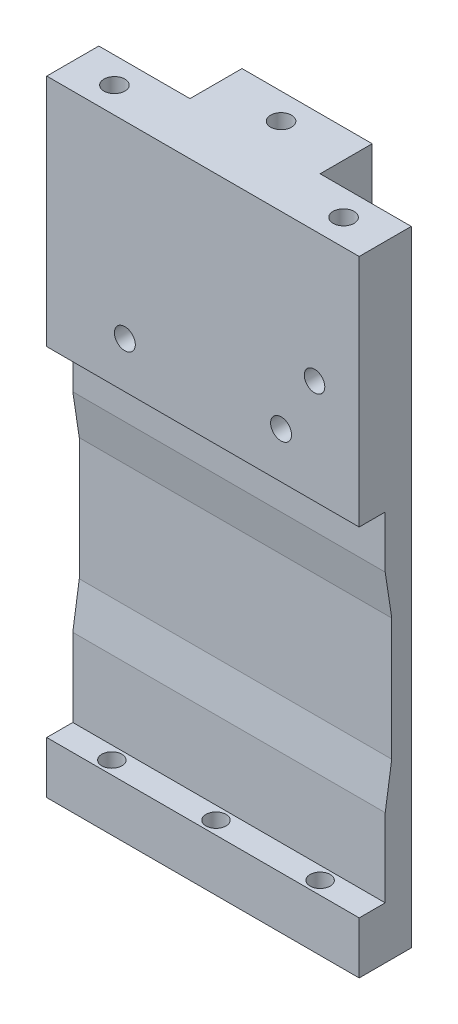
SolidWorks part; units mm, degrees
material "6061 Alloy"
ref_plane "Front Plane" through (0, 0, 0) normal (0, 0, 1) x (1, 0, 0)
ref_plane "Top Plane" through (0, 0, 0) normal (0, 1, 0) x (1, 0, 0)
ref_plane "Right Plane" through (0, 0, 0) normal (1, 0, 0) x (0, 0, -1)
sketch "Sketch1" plane through (0, 0, 0) normal (0, 1, 0) x (1, 0, 0)
  line L0 (-15.875, 6.35) -> (-15.875, 19.05)
  line L1 (38.1, -6.35) -> (-38.1, -6.35)
  line L2 (38.1, -6.35) -> (38.1, 6.35)
  line L3 (38.1, 6.35) -> (15.875, 6.35)
  line L4 (-38.1, -6.35) -> (-38.1, 6.35)
  line L5 (38.1, -6.35) -> (-38.1, 6.35) construction
  line L6 (38.1, 6.35) -> (-38.1, -6.35) construction
  line L7 (-15.875, 19.05) -> (15.875, 19.05)
  line L8 (15.875, 19.05) -> (15.875, 6.35)
  line L9 (-15.875, 6.35) -> (-38.1, 6.35)
  line L10 (0, 19.05) -> (0, 0) construction
  point P0 (0, 0)
  dimension "D1" = 76.2
  dimension "D2" = 12.7
  dimension "D3" = 31.75
  dimension "D4" = 12.7
extrude "Boss-Extrude1" add sketch "Sketch1" along normal mid plane 152.4
ref_plane "Plane1" through (0, 0, 0) normal (0, 1, 0) x (1, 0, 0)
sketch "Sketch5" plane through (0, 0, 0) normal (0, 1, 0) x (1, 0, 0)
  line L0 (-4.7625, 19.05) -> (-4.7625, 12.7)
  line L1 (15.875, 19.05) -> (-15.875, 19.05) construction
  line L2 (4.7625, 12.7) -> (4.7625, 19.05)
  line L3 (0, 0) -> (0, 12.7) construction
  line L4 (-4.7625, 19.05) -> (4.7625, 19.05)
  arc A0 (-4.7625, 12.7) -> (4.7625, 12.7) centre (0, 12.7) ccw
  point P10 (0, 7.9375)
  dimension "D1" = 11.1125
  dimension "D2" = 9.525
extrude "Cut-Extrude3" cut sketch "Sketch5" against normal mid plane 95.25
sketch "Sketch9" plane through (0, 0, 0) normal (1, 0, 0) x (0, 0, -1)
  line L0 (19.05, -52.3875) -> (12.7, -52.3875)
  line L1 (19.05, -52.3875) -> (19.05, -47.625)
  line L2 (19.05, -47.625) -> (7.9375, -47.625) construction
  line L3 (12.7, -52.3875) -> (12.7, -47.625) construction
  line L4 (7.9375, -47.625) -> (19.05, -47.625)
  arc A0 (12.7, -52.3875) -> (7.9375, -47.625) centre (12.7, -47.625) cw
  dimension "D2" = 90
  dimension "D1" = 4.7625
  dimension "D3" = 11.1125
revolve "Cut-Revolve1" cut sketch "Sketch9" angle 360 about L4
mirror "Mirror1" about plane through (0, 0, 0) normal (0, 1, 0) of "Cut-Revolve1"
ref_plane "Parting Plane" through (0, 0, 0) normal (0, 0, 1) x (1, 0, 0)
sketch "Sketch12" plane through (38.1, 0, 0) normal (1, 0, 0) x (0, 0, -1)
  line L0 (-6.35, -63.5) -> (0, -63.5)
  line L1 (-6.35, 76.2) -> (-6.35, -76.2) construction
  line L2 (0, 45.4834) -> (0, -45.4834) construction
  line L3 (0, -63.5) -> (0, -44.45)
  line L4 (0, -44.45) -> (1.5875, -33.9561)
  line L5 (1.5875, -33.9561) -> (1.5875, -4.1439)
  line L6 (1.5875, -4.1439) -> (0, 6.35)
  line L7 (0, 6.35) -> (0, 19.05)
  line L8 (0, 19.05) -> (-6.35, 19.05)
  line L9 (-6.35, 19.05) -> (-6.35, -63.5)
  line L10 (-6.35, -76.2) -> (6.35, -76.2) construction
  dimension "D1" = 19.05
  dimension "D2" = 12.7
  dimension "D3" = 82.55
  dimension "D4" = 1.5875
  dimension "D5" = 12.7
extrude "Cut-Extrude4" cut sketch "Sketch12" against normal through all
hole_wizard "#10 (0.1935) Diameter Hole1" positions "Sketch15" profile "Sketch16" hole size "#10" standard "ANSI Inch"
sketch "Sketch15" plane through (0, -76.2, 0) normal (0, -1, 0) x (-1, 0, 0)
  line L0 (38.1, 6.35) -> (38.1, -6.35) construction
  line L1 (-38.1, -6.35) -> (-38.1, 6.35) construction
  line L3 (25.4, -3.175) -> (-25.4, -3.175) construction
  line L4 (38.1, -6.35) -> (-38.1, -6.35) construction
  point P0 (25.4, -3.175)
  point P2 (-25.4, -3.175)
  point P16 (0, -3.175)
  dimension "D1" = 12.7
  dimension "D2" = 12.7
  dimension "D3" = 3.175
sketch "Sketch16" plane through (-25.4, -76.2, 3.175) normal (1, 0, 0) x (0, 0, -1)
  line L0 (0, 0) -> (0, 20.5266)
  line L1 (0, 20.5266) -> (2.4574, 19.05)
  line L2 (2.4574, 19.05) -> (2.4574, 0)
  line L5 (2.4574, 0) -> (0, 0)
  line L10 (0, 20.5266) -> (-2.4575, 19.05) construction
  line L11 (0, -6.35) -> (0, 107.95) construction
  dimension "Hole Dia." = 4.9149
  dimension "Hole Depth" = 19.05
  dimension "Drill Angle" = 118
hole_wizard "1/4-20 Tapped Hole1" positions "Sketch17" profile "Sketch18" tap size "1/4-20" standard "ANSI Inch" end condition through all
sketch "Sketch17" plane through (0, 76.2, 0) normal (0, 1, 0) x (1, 0, 0)
  line L0 (15.875, 19.05) -> (-15.875, 19.05) construction
  line L1 (15.875, 6.35) -> (15.875, 19.05) construction
  point P0 (0, 12.7)
  dimension "D1" = 6.35
  dimension "D2" = 15.875
sketch "Sketch18" plane through (0, 76.2, -12.7) normal (1, 0, 0) x (0, 0, 1)
  line L0 (0, 0) -> (0, 152.4)
  line L1 (0, 152.4) -> (2.5527, 152.4)
  line L2 (2.5527, 152.4) -> (2.5527, 0)
  line L5 (2.5527, 0) -> (0, 0)
  line L11 (0, -6.35) -> (0, 107.95) construction
  dimension "Thru Tap Drill Dia." = 5.1054
  dimension "Thru Tap Drill Depth" = 152.4
cosmetic thread "Hole Thread1" parameters "D2"=6.35
ref_plane "Plane2" through (0, -19.05, 0) normal (0, -1, 0) x (-1, 0, 0)
sketch "Sketch19" plane through (0, 0, -6.35) normal (0, 0, -1) x (-1, 0, 0)
  line L1 (-18.7294, -19.05) -> (18.7294, -19.05) construction
  circle A0 centre (-27.209, 44.45) radius 2.5
  dimension "D1" = 5
  dimension "D2" = 63.5
extrude "Cut-Extrude5" cut sketch "Sketch19" against normal through all
hole_wizard "1/4-20 Tapped Hole2" positions "Sketch20" profile "Sketch21" tap size "1/4-20" standard "ANSI Inch"
sketch "Sketch20" plane through (0, 76.2, 0) normal (0, 1, 0) x (1, 0, 0)
  point P0 (27.94, 0)
  point P3 (-27.94, 0)
sketch "Sketch21" plane through (27.94, 76.2, 0) normal (1, 0, 0) x (0, 0, 1)
  line L0 (0, 0) -> (0, 22.225)
  line L1 (0, 22.225) -> (2.5527, 20.6912)
  line L2 (2.5527, 20.6912) -> (2.5527, 0)
  line L5 (2.5527, 0) -> (0, 0)
  line L10 (0, 22.225) -> (-2.5527, 20.6912) construction
  line L11 (0, -6.35) -> (0, 107.95) construction
  dimension "Tap Drill Dia." = 5.1054
  dimension "Tap Drill Depth" = 22.225
  dimension "Drill Angle" = 118
cosmetic thread "Hole Thread2" parameters "D1"=38.26, "D2"=6.35
cosmetic thread "Hole Thread3" parameters "D1"=38.26, "D2"=6.35
hole_wizard "1/4-20 Tapped Hole3" positions "Sketch22" profile "Sketch23" tap size "1/4-20" standard "ANSI Inch"
sketch "Sketch22" plane through (0, 0, -19.05) normal (0, 0, -1) x (-1, 0, 0)
  line L0 (9.525, 57.15) -> (-9.525, 57.15) construction
  line L2 (0, 57.15) -> (0, 0) construction
  line L4 (-15.875, -76.2) -> (15.875, -76.2) construction
  line L5 (-9.525, 57.15) -> (-9.525, -66.675) construction
  line L7 (-9.525, -66.675) -> (9.525, -66.675) construction
  point P0 (-9.525, -66.675)
  point P2 (9.525, 57.15)
  point P4 (-9.525, 57.15)
  point P26 (9.525, -66.675)
  dimension "D1" = 19.05
  dimension "D2" = 123.825
  dimension "D3" = 9.525
  dimension "D4" = 19.05
sketch "Sketch23" plane through (9.525, -66.675, -19.05) normal (1, 0, 0) x (0, 1, 0)
  line L0 (0, 0) -> (0, 10.5838)
  line L1 (0, 10.5838) -> (2.5527, 9.05)
  line L2 (2.5527, 9.05) -> (2.5527, 0)
  line L5 (2.5527, 0) -> (0, 0)
  line L10 (0, 10.5838) -> (-2.5527, 9.05) construction
  line L11 (0, -6.35) -> (0, 107.95) construction
  dimension "Tap Drill Dia." = 5.1054
  dimension "Tap Drill Depth" = 9.05
  dimension "Drill Angle" = 118
cosmetic thread "Hole Thread4" parameters "D1"=38.26, "D2"=6.35
cosmetic thread "Hole Thread5" parameters "D1"=38.26, "D2"=6.35
cosmetic thread "Hole Thread6" parameters "D1"=38.26, "D2"=6.35
cosmetic thread "Hole Thread9" parameters "D1"=38.26, "D2"=6.35
hole_wizard "1/4-20 Tapped Hole4" positions "Sketch24" profile "Sketch25" tap size "1/4-20" standard "ANSI Inch"
sketch "Sketch24" plane through (0, 0, 6.35) normal (0, 0, 1) x (1, 0, 0)
  point P0 (19.05, 30.2607)
  point P3 (-19.05, 30.2607)
sketch "Sketch25" plane through (19.05, 30.2607, 6.35) normal (1, 0, 0) x (0, -1, 0)
  line L0 (0, 0) -> (0, 8.89)
  line L1 (0, 8.89) -> (2.5527, 7.3562)
  line L2 (2.5527, 7.3562) -> (2.5527, 0)
  line L5 (2.5527, 0) -> (0, 0)
  line L10 (0, 8.89) -> (-2.5527, 7.3562) construction
  line L11 (0, -6.35) -> (0, 107.95) construction
  dimension "Tap Drill Dia." = 5.1054
  dimension "Tap Drill Depth" = 8.89
  dimension "Drill Angle" = 118
cosmetic thread "Hole Thread7" parameters "D1"=12.7, "D2"=6.35
cosmetic thread "Hole Thread8" parameters "D1"=12.7, "D2"=6.35
